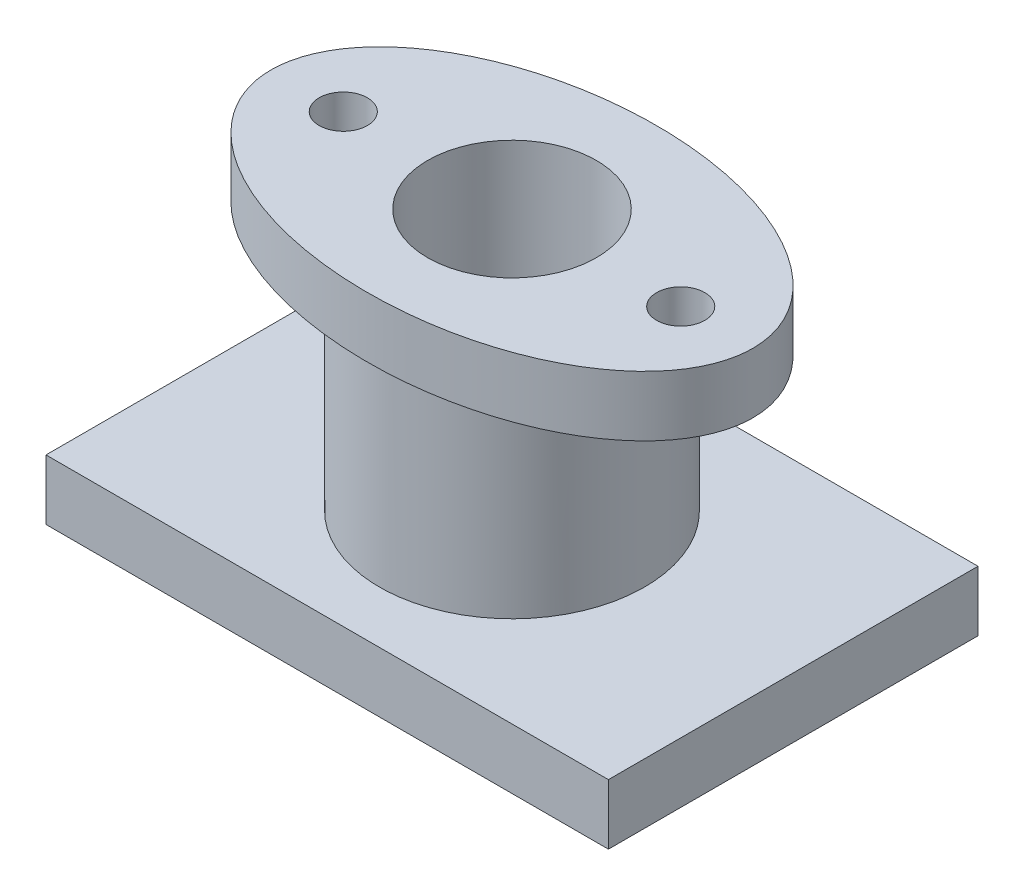
SolidWorks part; units mm, degrees
ref_plane "Front Plane" through (0, 0, 0) normal (0, 0, 1) x (1, 0, 0)
ref_plane "Top Plane" through (0, 0, 0) normal (0, 1, 0) x (1, 0, 0)
ref_plane "Right Plane" through (0, 0, 0) normal (1, 0, 0) x (0, 0, -1)
sketch "Sketch1" plane through (0, 0, 0) normal (0, 1, 0) x (1, 0, 0)
  line L1 (-70, -46) -> (70, -46)
  line L2 (-70, -46) -> (-70, 46)
  line L3 (-70, 46) -> (70, 46)
  line L4 (70, -46) -> (70, 46)
  circle A0 centre (0, 0) radius 16.5
  point P0 (0, 0)
  dimension "D3" = 33
  dimension "D1" = 92
  dimension "D2" = 140
extrude "Boss-Extrude2" add sketch "Sketch1" along normal blind 15
sketch "Sketch3" plane through (0, 15, 0) normal (0, 1, 0) x (1, 0, 0)
  circle A1 centre (0, 0) radius 33
  circle A2 centre (0, 0) radius 21
  dimension "D1" = 66
  dimension "D2" = 42
extrude "Boss-Extrude3" add sketch "Sketch3" along normal blind 50
sketch "Sketch4" plane through (0, 65, 0) normal (0, 1, 0) x (1, 0, 0)
  line L0 (0, 33) -> (0, -33) construction
  circle A0 centre (-42, 0) radius 6
  circle A1 centre (0, 0) radius 33 construction
  circle A2 centre (42, 0) radius 6
  circle A3 centre (0, 0) radius 21
  ellipse E0 centre (0, 0) end of major axis (60, 0) minor radius 36
  point P1 (-42, 0)
  point P7 (0, 0)
  point P16 (0, 0)
  dimension "D4" = 12
  dimension "D5" = 42
  dimension "D1" = 120
  dimension "D2" = 72
  dimension "D3" = 42
extrude "Boss-Extrude4" add sketch "Sketch4" along normal blind 15
